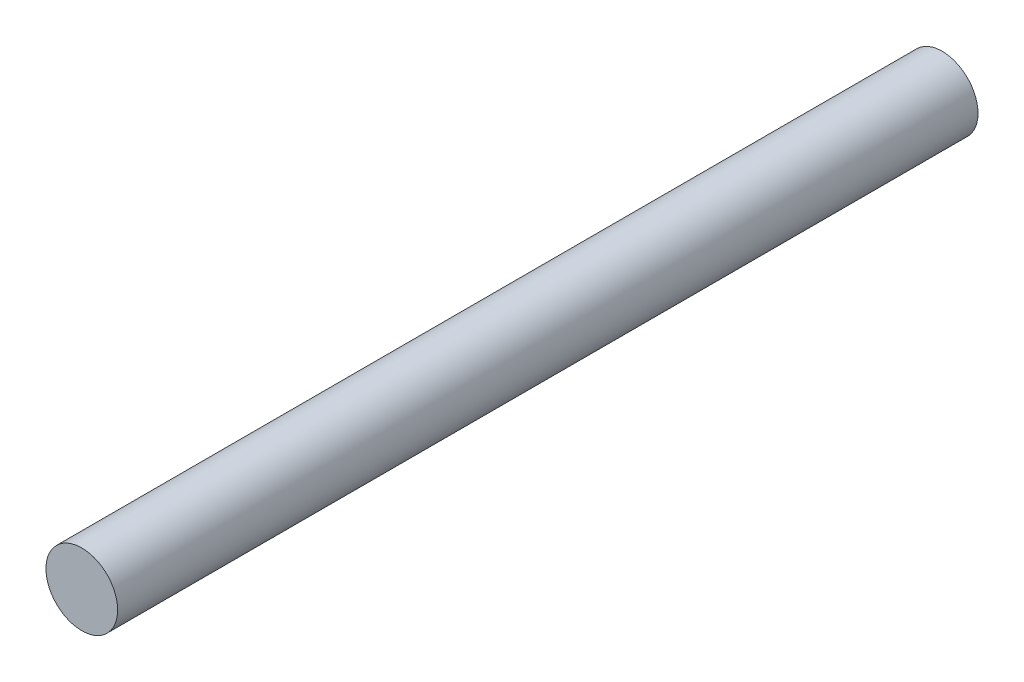
SolidWorks part; units mm, degrees
ref_plane "Front Plane" through (0, 0, 0) normal (0, 0, 1) x (1, 0, 0)
ref_plane "Top Plane" through (0, 0, 0) normal (0, 1, 0) x (1, 0, 0)
ref_plane "Right Plane" through (0, 0, 0) normal (1, 0, 0) x (0, 0, -1)
sketch "Sketch1" plane through (0, 0, 0) normal (0, 0, 1) x (1, 0, 0)
  circle A0 centre (0, 0) radius 2
extrude "Boss-Extrude1" add sketch "Sketch1" along normal blind 48
